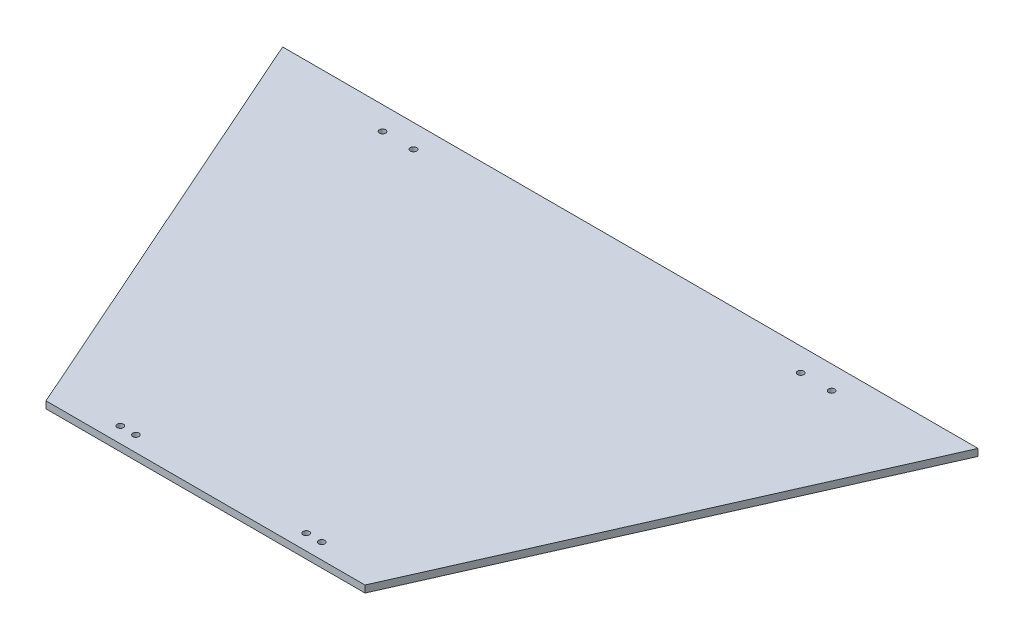
SolidWorks part; units mm, degrees
material "ABS PC"
ref_plane "前视基准面" through (0, 0, 0) normal (0, 0, 1) x (1, 0, 0)
ref_plane "上视基准面" through (0, 0, 0) normal (0, 1, 0) x (1, 0, 0)
ref_plane "右视基准面" through (0, 0, 0) normal (1, 0, 0) x (0, 0, -1)
sketch "草图1" plane through (0, 0, 0) normal (0, 1, 0) x (1, 0, 0)
  line L0 (0, 0) -> (0, 274.3) construction
  line L1 (-224.5, 274.3) -> (224.5, 274.3)
  line L2 (224.5, 274.3) -> (103, 0)
  line L3 (103, 0) -> (-103, 0)
  line L4 (-224.5, 274.3) -> (-103, 0)
  line L5 (224.5, 274.3) -> (224.5, 0) construction
  line L6 (224.5, 0) -> (103, 0) construction
  dimension "D1" = 449
  dimension "D2" = 274.3
  dimension "D3" = 206
extrude "凸台-拉伸1" add sketch "草图1" along normal blind 4.5
sketch "草图3" plane through (0, 4.5, 0) normal (0, 1, 0) x (1, 0, 0)
  line L0 (-145, 259.3) -> (-125, 259.3) construction
  line L1 (0, 0) -> (0, 274.3) construction
  line L2 (-103, 0) -> (103, 0) construction
  line L3 (224.5, 274.3) -> (-224.5, 274.3) construction
  line L4 (145, 259.3) -> (125, 259.3) construction
  line L5 (0, 10) -> (-65, 10) construction
  circle A0 centre (-145, 259.3) radius 2
  circle A1 centre (-125, 259.3) radius 2
  circle A2 centre (125, 259.3) radius 2
  circle A3 centre (145, 259.3) radius 2
  circle A4 centre (-65, 10) radius 2
  circle A5 centre (-55, 10) radius 2
  circle A6 centre (55, 10) radius 2
  circle A7 centre (65, 10) radius 2
  dimension "D1" = 4
  dimension "D2" = 4
  dimension "D7" = 4
  dimension "D8" = 4
  dimension "D3" = 15
  dimension "D4" = 20
  dimension "D5" = 250
  dimension "D6" = 10
  dimension "D9" = 55
  dimension "D10" = 10
extrude "切除-拉伸1" cut sketch "草图3" against normal blind 10
